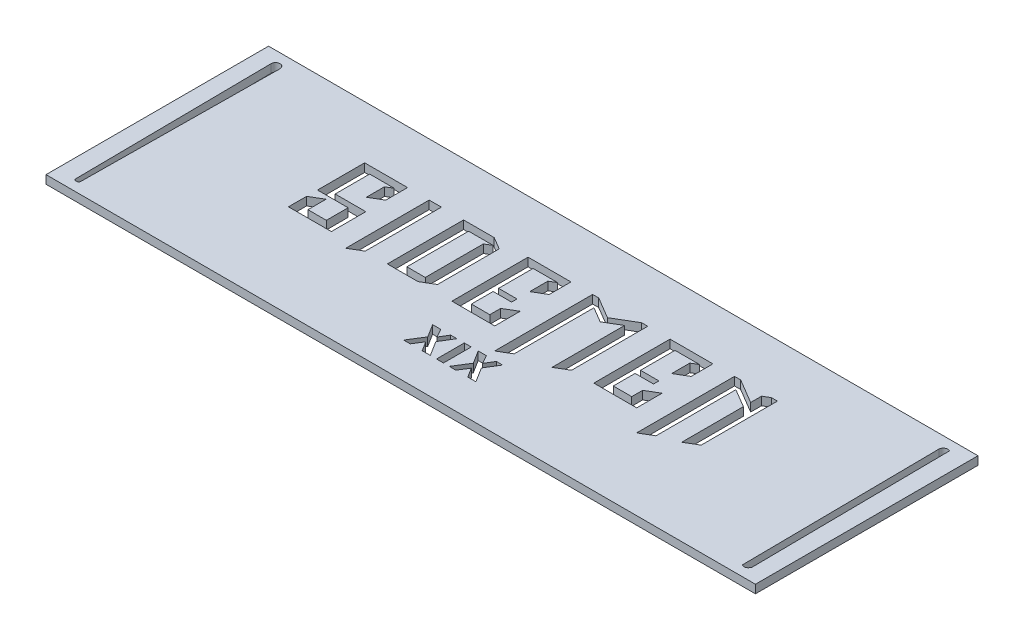
SolidWorks part; units mm, degrees
ref_plane "Front Plane" through (0, 0, 0) normal (0, 0, 1) x (1, 0, 0)
ref_plane "Top Plane" through (0, 0, 0) normal (0, 1, 0) x (1, 0, 0)
ref_plane "Right Plane" through (0, 0, 0) normal (1, 0, 0) x (0, 0, -1)
sketch "Sketch1" plane through (0, 0, 0) normal (0, 1, 0) x (1, 0, 0)
  line L1 (-127.5, -40) -> (127.5, -40)
  line L2 (-127.5, -40) -> (-127.5, 40)
  line L3 (-127.5, 40) -> (127.5, 40)
  line L4 (127.5, -40) -> (127.5, 40)
  line L5 (-127.5, -40) -> (127.5, 40) construction
  line L6 (-127.5, 40) -> (127.5, -40) construction
  point P0 (0, 0)
  dimension "D1" = 80
  dimension "D2" = 255
extrude "Boss-Extrude1" add sketch "Sketch1" along normal blind 3
sketch "Sketch2" plane through (0, 3, 0) normal (0, 1, 0) x (1, 0, 0)
  line L0 (-127.5, 40) -> (-127.5, -40) construction
  line L1 (127.5, 40) -> (-127.5, 40) construction
  line L2 (-127.5, -40) -> (127.5, -40) construction
  line L3 (127.5, -40) -> (127.5, 40) construction
  line L4 (-121.6, 35) -> (-120.8625, -36.3476)
  line L5 (-118.4, 35) -> (-119.1375, -36.3476)
  line L6 (118.4, 35) -> (119.1375, -36.3476)
  line L7 (121.6, -35) -> (120.8625, 36.3476)
  arc A0 (-118.4, 35) -> (-121.6, 35) centre (-120, 35) ccw
  arc A1 (-120.8625, -36.3476) -> (-119.1375, -36.3476) centre (-120, -35) ccw
  arc A2 (119.1375, -36.3476) -> (121.6, -35) centre (120, -35) ccw
  arc A3 (120.8625, 36.3476) -> (118.4, 35) centre (120, 35) ccw
  dimension "D1" = 3.2
  dimension "D2" = 3.2
  dimension "D3" = 3.2
  dimension "D4" = 3.2
  dimension "D6" = 5
  dimension "D7" = 7.5
  dimension "D8" = 5
  dimension "D9" = 7.5
  dimension "D10" = 5
  dimension "D12" = 7.5
  dimension "D5" = 7.5
  dimension "D11" = 5
extrude "Cut-Extrude1" cut sketch "Sketch2" against normal up to next
sketch "Sketch5" plane through (0, 3, 0) normal (0, 1, 0) x (1, 0, 0)
  text T0 "XIX" font "Franklin Gothic Demi" height 10
extrude "Cut-Extrude3" cut sketch "Sketch5" against normal up to next
sketch "Sketch6" plane through (0, 3, 0) normal (0, 1, 0) x (1, 0, 0)
  text T0 "SIDEMEN" font "Burdeles" height 30
extrude "Cut-Extrude4" cut sketch "Sketch6" against normal up to next
